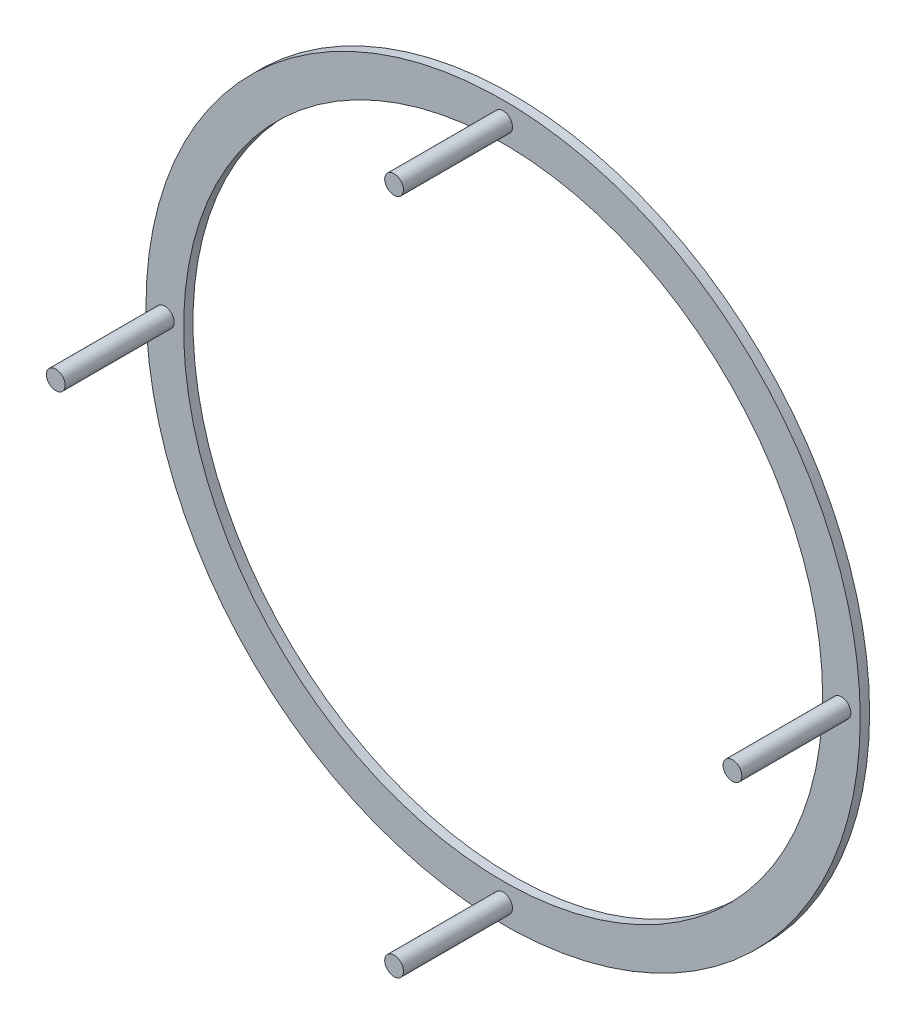
SolidWorks part; units mm, degrees
ref_plane "前视基准面" through (0, 0, 0) normal (0, 0, 1) x (1, 0, 0)
ref_plane "上视基准面" through (0, 0, 0) normal (0, 1, 0) x (1, 0, 0)
ref_plane "右视基准面" through (0, 0, 0) normal (1, 0, 0) x (0, 0, -1)
sketch "草图1" plane through (0, 0, 0) normal (0, 0, 1) x (1, 0, 0)
  circle A0 centre (0, 0) radius 190
  circle A1 centre (0, 0) radius 170
  dimension "D1" = 340
  dimension "D2" = 380
extrude "凸台-拉伸2" add sketch "草图1" along normal blind 5
sketch "草图2" plane through (0, 0, 5) normal (0, 0, 1) x (1, 0, 0)
  line L0 (0, 0) -> (0, 180) construction
  line L1 (0, 0) -> (0, -180) construction
  line L2 (-180, 0) -> (0, 0) construction
  line L3 (0, 0) -> (180, 0) construction
  circle A0 centre (0, 180) radius 5
  circle A1 centre (-180, 0) radius 5
  circle A2 centre (0, -180) radius 5
  circle A3 centre (180, 0) radius 5
extrude "凸台-拉伸3" add sketch "草图2" along normal blind 58
